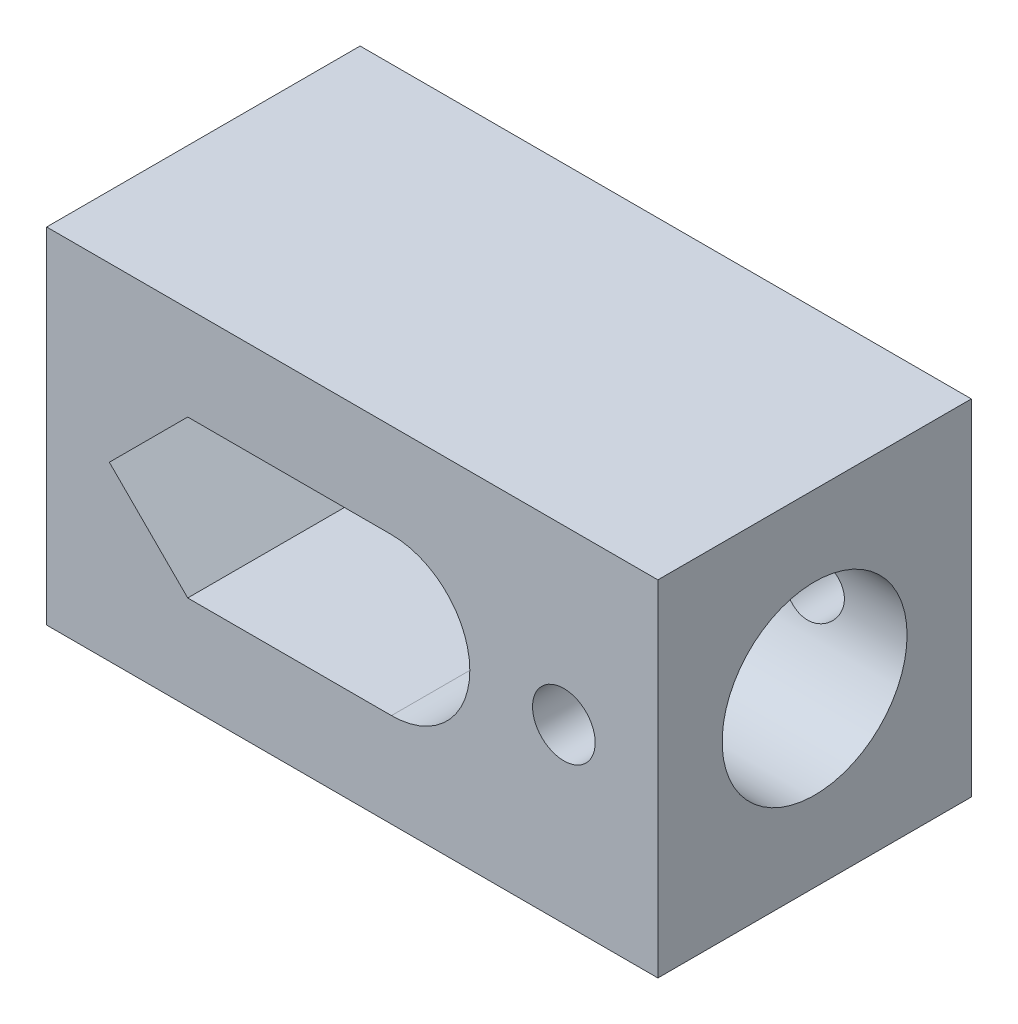
SolidWorks part; units mm, degrees
material "1060 合金"
ref_plane "前视基准面" through (0, 0, 0) normal (0, 0, 1) x (1, 0, 0)
ref_plane "上视基准面" through (0, 0, 0) normal (0, 1, 0) x (1, 0, 0)
ref_plane "右视基准面" through (0, 0, 0) normal (1, 0, 0) x (0, 0, -1)
sketch "草图1" plane through (0, 0, 0) normal (0, 0, 1) x (1, 0, 0)
  line L0 (0, 0) -> (-30.1084, 0) construction
  line L1 (9.75, -5.5) -> (-9.75, -5.5)
  line L2 (9.75, -5.5) -> (9.75, 5.5)
  line L3 (9.75, 5.5) -> (-9.75, 5.5)
  line L4 (-9.75, -5.5) -> (-9.75, 5.5)
  line L5 (9.75, -5.5) -> (-9.75, 5.5) construction
  line L6 (9.75, 5.5) -> (-9.75, -5.5) construction
  line L7 (-5.25, 2.5) -> (-7.75, 0)
  line L8 (-5.25, -2.5) -> (1.25, -2.5)
  line L9 (-5.25, -2.5) -> (-5.25, 2.5) construction
  line L10 (-5.25, 2.5) -> (1.25, 2.5)
  line L11 (1.25, -2.5) -> (1.25, 2.5) construction
  line L12 (-5.25, -2.5) -> (1.25, 2.5) construction
  line L13 (-5.25, 2.5) -> (1.25, -2.5) construction
  line L14 (-7.75, 0) -> (-5.25, -2.5)
  arc A0 (1.25, 2.5) -> (1.25, -2.5) centre (1.25, 0) cw
  point P0 (0, 0)
  point P8 (-2, 0)
  dimension "D1" = 6.5
  dimension "D4" = 2
  dimension "D3" = 3
  dimension "D2" = 5
extrude "凸台-拉伸1" add sketch "草图1" along normal mid plane 10
sketch "草图2" plane through (9.75, 0, 0) normal (1, 0, 0) x (0, 0, -1)
  circle A0 centre (0, 0) radius 2.95
  dimension "D1" = 5.9
extrude "切除-拉伸1" cut sketch "草图2" against normal blind 5
hole_wizard "Ø2.0 (2) 直径孔1" positions "草图4" profile "草图3" hole size "Ø2.0" standard "GB" end condition through all
sketch "草图4" plane through (0, 0, 5) normal (0, 0, 1) x (1, 0, 0)
  line L0 (6.75, 0) -> (0, 0) construction
  line L2 (9.75, -5.5) -> (9.75, 5.5) construction
  point P0 (6.75, 0)
  dimension "D1" = 3
sketch "草图3" plane through (6.75, 0, 5) normal (1, 0, 0) x (0, -1, 0)
  line L0 (0, 0) -> (0, 10)
  line L1 (0, 10) -> (1, 10)
  line L2 (1, 10) -> (1, 0)
  line L5 (1, 0) -> (0, 0)
  line L11 (0, -6.35) -> (0, 107.95) construction
  dimension "通孔孔直径" = 2
  dimension "通孔孔深度" = 10
move or copy body "实体-移动/复制1" [suppressed] bodies to move or copy 108
